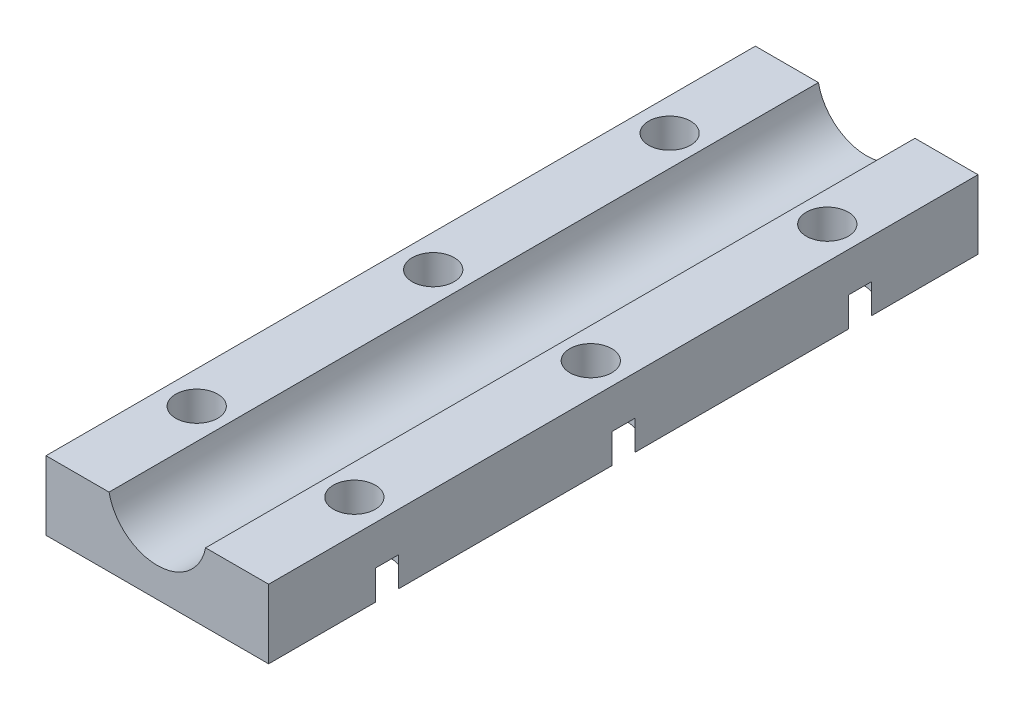
SolidWorks part; units mm, degrees
material "ABS"
ref_plane "Front Plane" through (0, 0, 0) normal (0, 0, 1) x (1, 0, 0)
ref_plane "Top Plane" through (0, 0, 0) normal (0, 1, 0) x (1, 0, 0)
ref_plane "Right Plane" through (0, 0, 0) normal (1, 0, 0) x (0, 0, -1)
sketch "Sketch1" plane through (0, 0, 0) normal (0, 0, 1) x (1, 0, 0)
  line L0 (33.3375, -1.5875) -> (-48.7363, -1.5875) construction
  line L1 (7.7771, -1.5875) -> (17.9371, -1.5875)
  line L2 (17.9371, -1.5875) -> (17.9371, -14.2875)
  line L3 (17.9371, -14.2875) -> (-17.9371, -14.2875)
  line L4 (-17.9371, -14.2875) -> (-17.9371, -1.5875)
  line L5 (-17.9371, -1.5875) -> (-7.7771, -1.5875)
  arc A0 (7.7771, -1.5875) -> (-7.7771, -1.5875) centre (0, 0) cw
  dimension "D1" = 1.5875
  dimension "D2" = 7.9375
  dimension "D3" = 12.7
  dimension "D4" = 10.16
extrude "stock" add sketch "Sketch1" along normal blind 114.3 contours L4 L5 A0 L1 L2 L3
hole_wizard "1/4 Clearance Hole1" positions "Sketch2" profile "Sketch3" hole size "1/4" standard "ANSI Inch"
sketch "Sketch2" plane through (0, -3.175, 0) normal (0, 1, 0) x (1, 0, 0)
  line L0 (-12.7, -19.05) -> (-12.7, -57.15) construction
  line L1 (-12.7, -57.15) -> (-12.7, -95.25) construction
  line L2 (12.7, -95.25) -> (12.7, -57.15) construction
  line L3 (12.7, -57.15) -> (12.7, -19.05) construction
  line L4 (12.7, -57.15) -> (-12.7, -57.15) construction
  line L12 (0, 0) -> (0, -57.15) construction
  line L13 (-12.7, -57.15) -> (-17.4348, -57.15) construction
  line L14 (-17.4348, -114.3) -> (-17.4348, 0) construction
  point P0 (-12.7, -19.05)
  point P2 (-12.7, -57.15)
  point P4 (-12.7, -95.25)
  point P6 (12.7, -95.25)
  point P8 (12.7, -57.15)
  point P10 (12.7, -19.05)
  dimension "D1" = 38.1
  dimension "D2" = 25.4
sketch "Sketch3" plane through (-12.7, -3.175, 19.05) normal (1, 0, 0) x (0, 0, 1)
  line L0 (0, 0) -> (0, 12.7)
  line L1 (0, 12.7) -> (3.3782, 12.7)
  line L2 (3.3782, 12.7) -> (3.3782, 0)
  line L5 (3.3782, 0) -> (0, 0)
  line L11 (0, -6.35) -> (0, 107.95) construction
  dimension "Thru Hole Dia." = 6.7564
  dimension "Thru Hole Depth" = 12.7
hole_wizard "O (0.316) Diameter Hole1" positions "Sketch4" profile "Sketch5" hole size "O" standard "ANSI Inch"
sketch "Sketch4" plane through (0, -3.175, 0) normal (0, 1, 0) x (1, 0, 0)
  point P0 (-12.7, -95.25)
  point P3 (-12.7, -57.15)
  point P6 (-12.7, -19.05)
  point P9 (12.7, -19.05)
  point P12 (12.7, -57.15)
  point P15 (12.7, -95.25)
sketch "Sketch5" plane through (-12.7, -3.175, 95.25) normal (1, 0, 0) x (0, 0, 1)
  line L0 (0, 0) -> (0, 12.7)
  line L1 (0, 12.7) -> (4.0132, 12.7)
  line L2 (4.0132, 12.7) -> (4.0132, 0.635)
  line L3 (4.0132, 0.635) -> (4.6482, 0)
  line L5 (4.6482, 0) -> (0, 0)
  line L6 (-4.0132, 0.635) -> (-4.6482, 0) construction
  line L11 (0, -6.35) -> (0, 107.95) construction
  dimension "Thru Hole Dia." = 8.0264
  dimension "Thru Hole Depth" = 12.7
  dimension "Near C'Sink Dia." = 9.2964
  dimension "Near C'Sink Angle" = 90
hole_wizard "CBORE for 1/4 Socket Head Cap Screw1" positions "Sketch6" profile "Sketch7" counterbore size "1/4" standard "ANSI Inch" end condition up to next
sketch "Sketch6" plane through (0, -14.2875, 0) normal (0, -1, 0) x (-1, 0, 0)
  point P0 (12.7, -19.05)
  point P2 (12.7, -57.15)
  point P4 (12.7, -95.25)
  point P6 (-12.7, -95.25)
  point P8 (-12.7, -57.15)
  point P10 (-12.7, -19.05)
sketch "Sketch7" plane through (-12.7, -14.2875, 19.05) normal (1, 0, 0) x (0, 0, -1)
  line L0 (0, 0) -> (0, 12.7)
  line L1 (0, 12.7) -> (3.3782, 12.7)
  line L3 (3.3782, 12.7) -> (3.3782, 6.35)
  line L4 (3.3782, 6.35) -> (5.5562, 6.35)
  line L5 (5.5562, 6.35) -> (5.5562, 0)
  line L7 (5.5562, 0) -> (0, 0)
  line L11 (0, -6.35) -> (0, 107.95) construction
  dimension "Thru Hole Dia." = 6.7564
  dimension "Thru Hole Depth" = 12.7
  dimension "C'Bore Dia." = 11.1125
  dimension "C'Bore Depth" = 6.35
chamfer "Chamfer1" distance 1.5875 angle 45 16 edges at (-17.9371, -14.2875, 8.597) (-17.9371, -14.2875, 105.703) (0, -14.2875, 114.3) (17.9371, -14.2875, 8.597) (17.9371, -14.2875, 105.703) (0, -14.2875, 0) (-17.9371, -14.2875, 38.1) (-7.1437, -14.2875, 57.15) (-17.9371, -14.2875, 76.2) (-7.1437, -14.2875, 95.25) (7.1438, -14.2875, 95.25) (17.9371, -14.2875, 76.2) (7.1438, -14.2875, 57.15) (17.9371, -14.2875, 38.1) (7.1438, -14.2875, 19.05) (-7.1438, -14.2875, 19.05)
